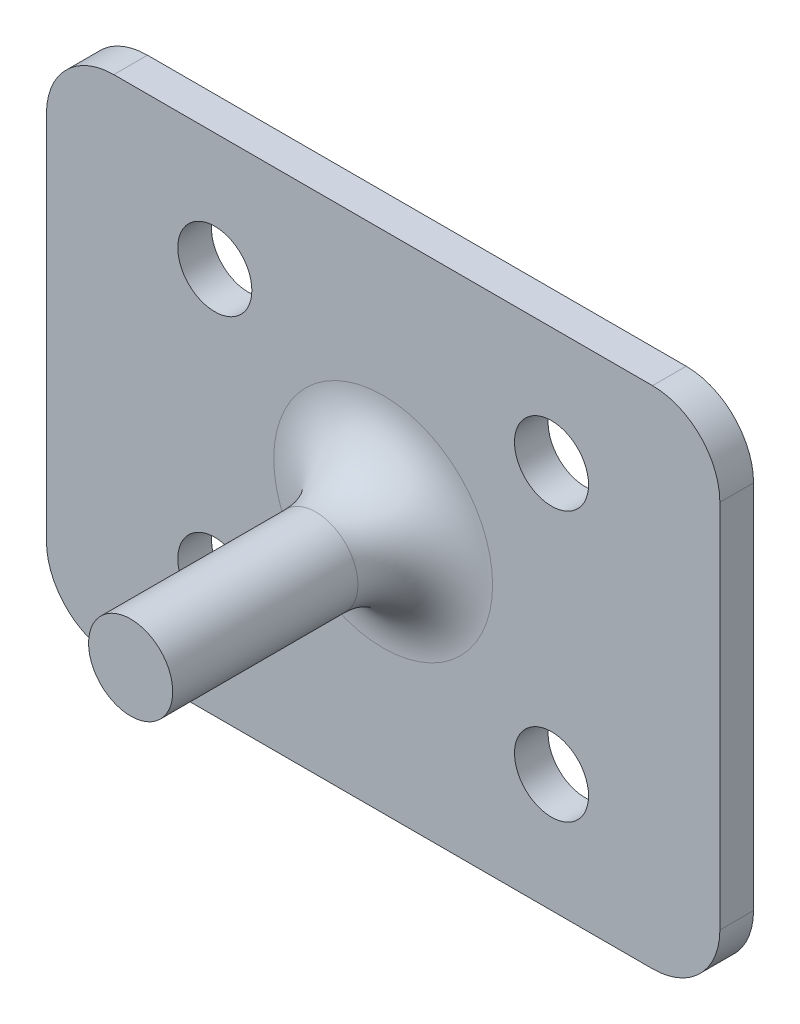
SolidWorks part; units mm, degrees
ref_plane "Front Plane" through (0, 0, 0) normal (0, 0, 1) x (1, 0, 0)
ref_plane "Top Plane" through (0, 0, 0) normal (0, 1, 0) x (1, 0, 0)
ref_plane "Right Plane" through (0, 0, 0) normal (1, 0, 0) x (0, 0, -1)
sketch "Sketch1" plane through (0, 0, 0) normal (0, 0, 1) x (1, 0, 0)
  line L1 (16.51, -12.7) -> (57.15, -12.7)
  line L2 (11.43, -17.78) -> (11.43, -45.72)
  line L3 (16.51, -50.8) -> (57.15, -50.8)
  line L4 (62.23, -17.78) -> (62.23, -45.72)
  arc A0 (11.43, -45.72) -> (16.51, -50.8) centre (16.51, -45.72) ccw
  arc A1 (57.15, -50.8) -> (62.23, -45.72) centre (57.15, -45.72) ccw
  arc A2 (57.15, -12.7) -> (62.23, -17.78) centre (57.15, -17.78) cw
  arc A3 (16.51, -12.7) -> (11.43, -17.78) centre (16.51, -17.78) ccw
  dimension "D5" = 5.08
  dimension "D1" = 38.1
  dimension "D2" = 50.8
extrude "Boss-Extrude1" add sketch "Sketch1" along normal blind 2.54
sketch "Sketch2" plane through (0, 0, 2.54) normal (0, 0, 1) x (1, 0, 0)
  line L0 (57.15, -12.7) -> (16.51, -12.7) construction
  line L1 (11.43, -17.78) -> (11.43, -45.72) construction
  circle A0 centre (24.13, -21.59) radius 2.794
  circle A1 centre (49.53, -21.59) radius 2.794
  circle A2 centre (24.13, -41.91) radius 2.794
  circle A3 centre (49.53, -41.91) radius 2.794
  dimension "D1" = 5.588
  dimension "D2" = 5.588
  dimension "D3" = 5.588
  dimension "D4" = 5.588
  dimension "D5" = 25.4
  dimension "D6" = 20.32
  dimension "D7" = 20.32
  dimension "D8" = 25.4
  dimension "D9" = 8.89
  dimension "D11" = 12.7
extrude "Cut-Extrude1" cut sketch "Sketch2" against normal through all
sketch "Sketch3" plane through (0, 0, 2.54) normal (0, 0, 1) x (1, 0, 0)
  line L0 (36.83, -12.7) -> (36.83, -50.8) construction
  line L1 (57.15, -12.7) -> (16.51, -12.7) construction
  line L2 (16.51, -50.8) -> (57.15, -50.8) construction
  line L3 (11.43, -31.75) -> (62.23, -31.75) construction
  line L4 (11.43, -17.78) -> (11.43, -45.72) construction
  line L5 (62.23, -45.72) -> (62.23, -17.78) construction
  circle A0 centre (36.83, -31.75) radius 3.175
  dimension "D1" = 6.35
extrude "Boss-Extrude2" add sketch "Sketch3" along normal blind 19.05
sketch "Sketch4" plane through (0, 0, 21.59) normal (0, 0, 1) x (1, 0, 0)
  line L0 (36.83, -31.75) -> (36.83, -22.5538) construction
fillet "Fillet1" radius 5.08 1 edges at (40.005, -31.75, 2.54)
